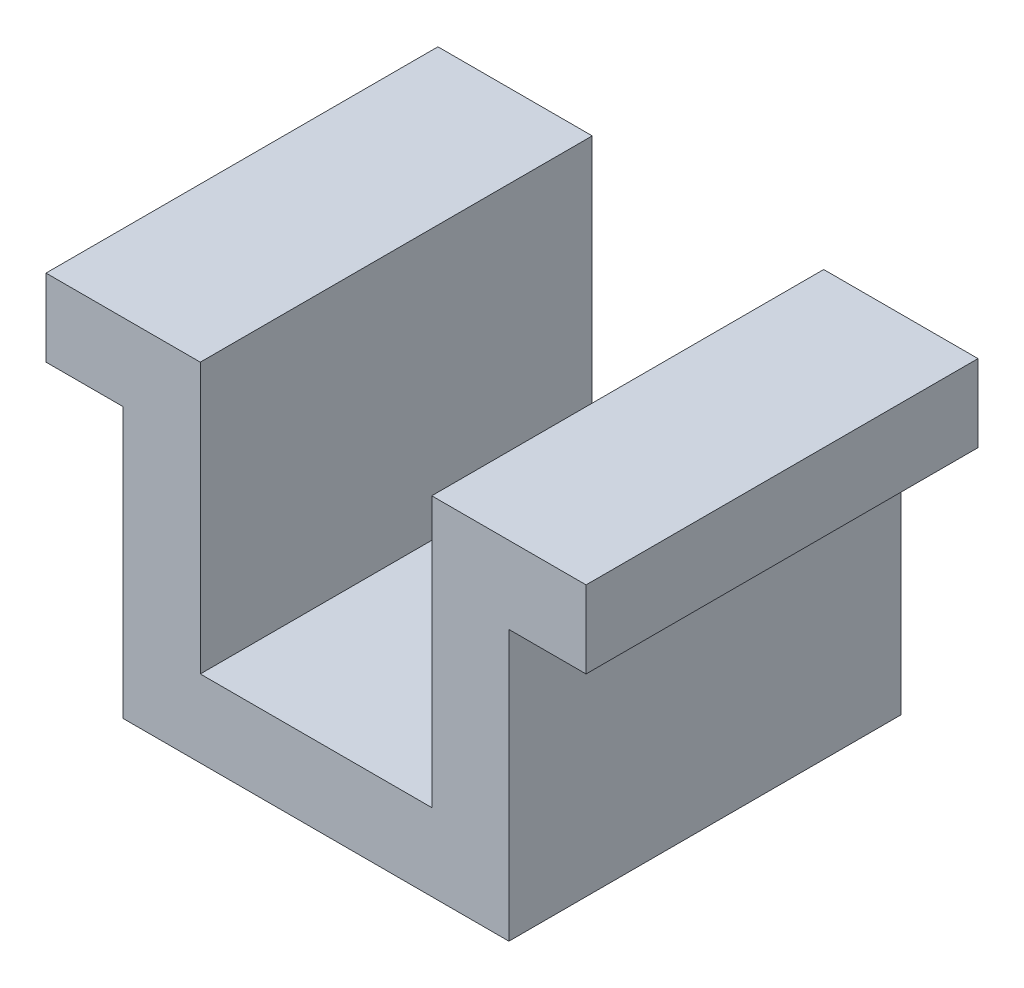
SolidWorks part; units mm, degrees
material "Aleación 6061"
ref_plane "Alzado" through (0, 0, 0) normal (0, 0, 1) x (1, 0, 0)
ref_plane "Planta" through (0, 0, 0) normal (0, 1, 0) x (1, 0, 0)
ref_plane "Vista lateral" through (0, 0, 0) normal (1, 0, 0) x (0, 0, -1)
sketch "Croquis1" plane through (0, 0, 0) normal (0, 0, 1) x (1, 0, 0)
  line L0 (0, 0) -> (50, 0)
  line L1 (50, 0) -> (50, 35)
  line L2 (50, 35) -> (60, 35)
  line L3 (0, 0) -> (0, 35)
  line L4 (0, 35) -> (-10, 35)
  dimension "D1" = 35
  dimension "D2" = 50
  dimension "D3" = 10
extrude "Extruir-Lámina1" add sketch "Croquis1" along normal mid plane 50.8 thin thin type one direction reverse wall 10
sketch "Croquis2" plane through (0, 10, 0) normal (0, 1, 0) x (1, 0, 0)
  line L0 (25, 25.4) -> (25, -25.4) construction
  line L1 (10, 25.4) -> (40, 25.4) construction
  line L2 (10, -25.4) -> (40, -25.4) construction
  line L3 (0, 0) -> (40, 0) construction
  line L4 (40, -25.4) -> (40, 25.4) construction
  circle A0 centre (25, 0) radius 4.7625
  dimension "D1" = 9.525
extrude "Cortar-Extruir1" cut sketch "Croquis2" against normal through all
